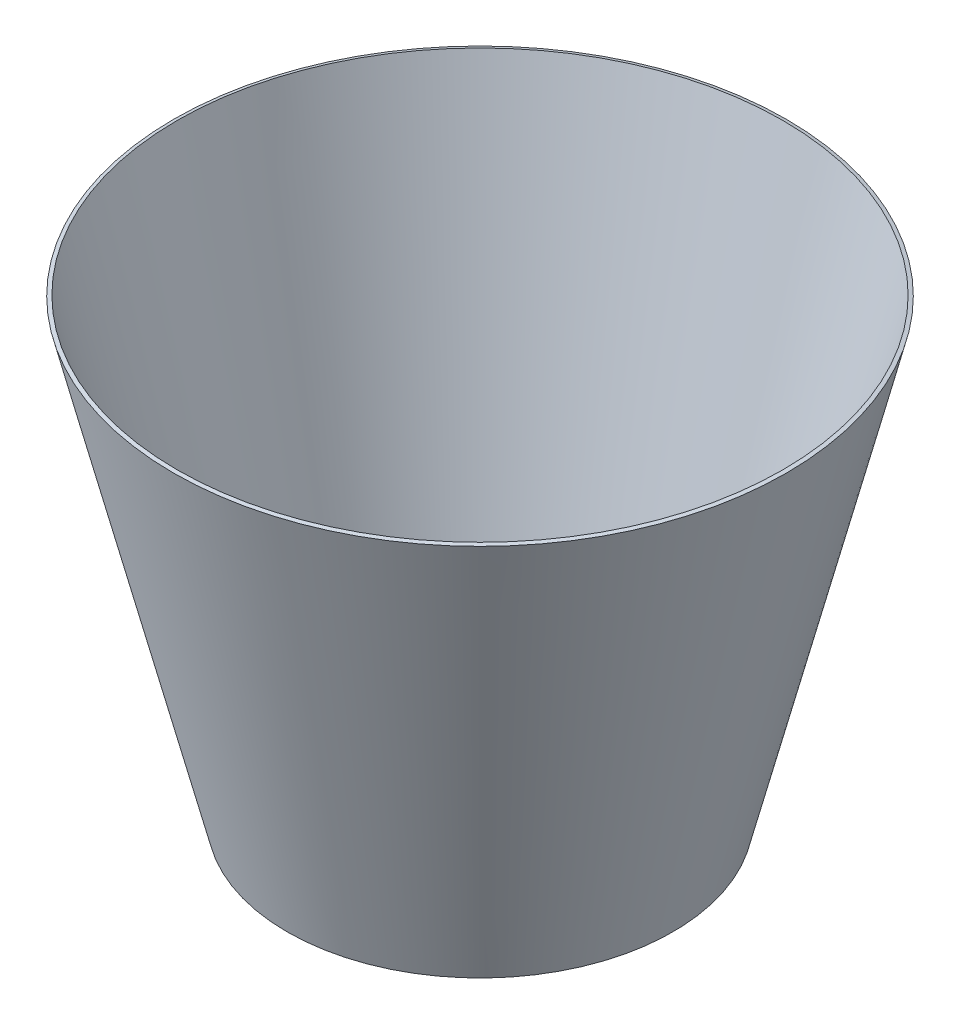
SolidWorks part; units mm, degrees
ref_plane "Front Plane" through (0, 0, 0) normal (0, 0, 1) x (1, 0, 0)
ref_plane "Top Plane" through (0, 0, 0) normal (0, 1, 0) x (1, 0, 0)
ref_plane "Right Plane" through (0, 0, 0) normal (1, 0, 0) x (0, 0, -1)
sketch "Sketch1" plane through (0, 0, 0) normal (0, 0, 1) x (1, 0, 0)
  line L0 (0, 168.0544) -> (0, -246.3263) construction
  line L1 (127, -251.8514) -> (203.2, 52.9486)
  dimension "D1" = 304.8
  dimension "D2" = 127
  dimension "D3" = 203.2
revolve "Revolve-Thin1" add sketch "Sketch1" angle 360 about L0
